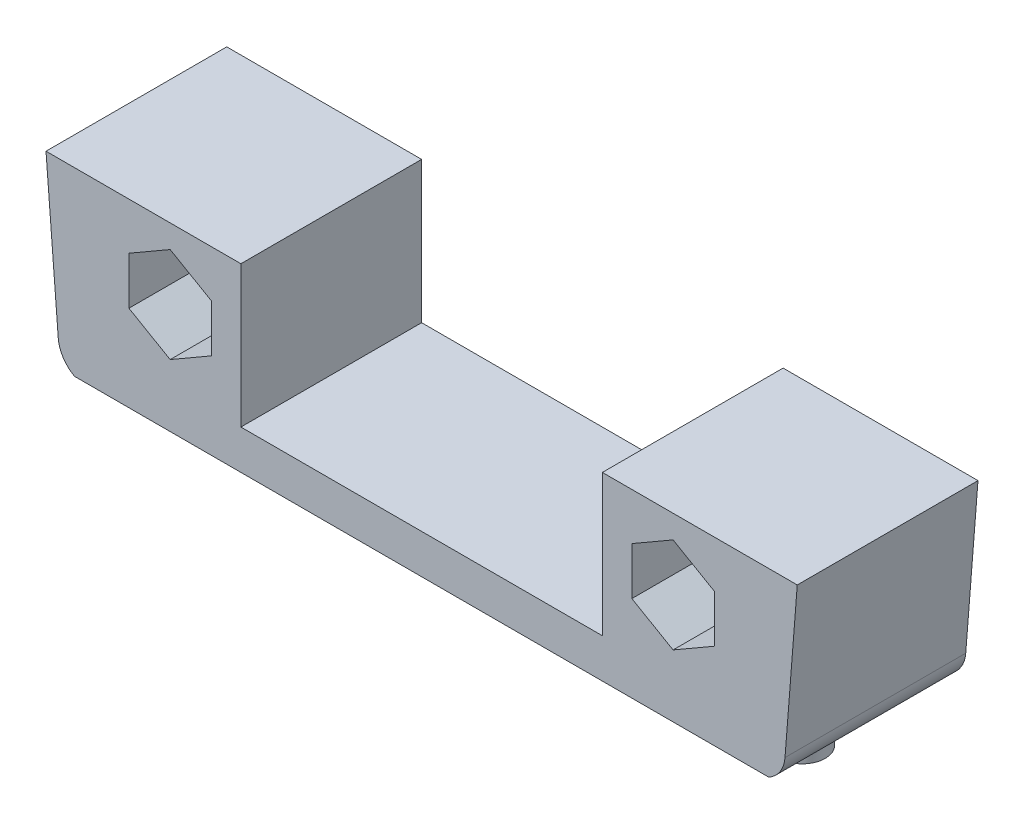
SolidWorks part; units mm, degrees
ref_plane "Front Plane" through (0, 0, 0) normal (0, 0, 1) x (1, 0, 0)
ref_plane "Top Plane" through (0, 0, 0) normal (0, 1, 0) x (1, 0, 0)
ref_plane "Right Plane" through (0, 0, 0) normal (1, 0, 0) x (0, 0, -1)
sketch "Sketch1" plane through (0, 0, 0) normal (0, 0, 1) x (1, 0, 0)
  line L0 (-23.9007, -76.5) -> (23.9007, -76.5)
  line L1 (-16, -84.0311) -> (-13.375, -82.5155)
  line L2 (-13.375, -82.5155) -> (-13.375, -79.4845)
  line L3 (-13.375, -79.4845) -> (-16, -77.9689)
  line L4 (-16, -77.9689) -> (-18.625, -79.4845)
  line L5 (-18.625, -79.4845) -> (-18.625, -82.5155)
  line L6 (-18.625, -82.5155) -> (-16, -84.0311)
  line L7 (16, -84.0311) -> (18.625, -82.5155)
  line L8 (18.625, -82.5155) -> (18.625, -79.4845)
  line L9 (18.625, -79.4845) -> (16, -77.9689)
  line L10 (16, -77.9689) -> (13.375, -79.4845)
  line L11 (13.375, -79.4845) -> (13.375, -82.5155)
  line L12 (13.375, -82.5155) -> (16, -84.0311)
  line L13 (-20.5, -85.5) -> (-11.5, -85.5)
  line L14 (-20.5, -85.5) -> (-20.5, -76.5)
  line L15 (-20.5, -76.5) -> (-11.5, -76.5)
  line L16 (-11.5, -85.5) -> (-11.5, -76.5)
  line L17 (-20.5, -85.5) -> (-11.5, -76.5) construction
  line L18 (-24.5714, 68.9048) -> (-33.6515, 43.9576)
  line L19 (-33.4302, 42.1552) -> (-25.3419, 30.1639)
  line L20 (-25, 29.0455) -> (-25, -29.0455)
  line L21 (-25.3419, -30.1639) -> (-33.4302, -42.1552)
  line L22 (-33.6515, -43.9576) -> (-24.5714, -68.9048)
  line L23 (-24.457, -69.4319) -> (-23.1215, -86.4007)
  line L24 (-21.475, -88.2134) -> (0, -92)
  line L25 (0, -92) -> (21.475, -88.2134)
  line L26 (23.1215, -86.4007) -> (24.457, -69.4319)
  line L27 (24.5714, -68.9048) -> (33.6515, -43.9576)
  line L28 (33.4302, -42.1552) -> (25.3419, -30.1639)
  line L29 (25, -29.0455) -> (25, 29.0455)
  line L30 (25.3419, 30.1639) -> (33.4302, 42.1552)
  line L31 (33.6515, 43.9576) -> (24.5714, 68.9048)
  line L32 (24.457, 69.4319) -> (23.1215, 86.4007)
  line L33 (21.475, 88.2134) -> (0, 92)
  line L34 (0, 92) -> (-21.475, 88.2134)
  line L35 (-23.1215, 86.4007) -> (-24.457, 69.4319)
  line L36 (-24.5714, 68.9048) -> (-33.6515, 43.9576)
  line L37 (-33.4302, 42.1552) -> (-25.3419, 30.1639)
  line L38 (-25, 29.0455) -> (-25, -29.0455)
  line L39 (-25.3419, -30.1639) -> (-33.4302, -42.1552)
  line L40 (-33.6515, -43.9576) -> (-24.5714, -68.9048)
  line L41 (-24.457, -69.4319) -> (-23.1215, -86.4007)
  line L42 (-21.475, -88.2134) -> (0, -92)
  line L43 (0, -92) -> (21.475, -88.2134)
  line L44 (23.1215, -86.4007) -> (24.457, -69.4319)
  line L45 (24.5714, -68.9048) -> (33.6515, -43.9576)
  line L46 (33.4302, -42.1552) -> (25.3419, -30.1639)
  line L47 (25, -29.0455) -> (25, 29.0455)
  line L48 (25.3419, 30.1639) -> (33.4302, 42.1552)
  line L49 (33.6515, 43.9576) -> (24.5714, 68.9048)
  line L50 (24.457, 69.4319) -> (23.1215, 86.4007)
  line L51 (21.475, 88.2134) -> (0, 92)
  line L52 (0, 92) -> (-21.475, 88.2134)
  line L53 (-23.1215, 86.4007) -> (-24.457, 69.4319)
  line L54 (-20.5, -76.5) -> (-11.5, -85.5) construction
  line L55 (20.5, -76.5) -> (11.5, -76.5)
  line L56 (20.5, -76.5) -> (20.5, -85.5)
  line L57 (20.5, -85.5) -> (11.5, -85.5)
  line L58 (11.5, -76.5) -> (11.5, -85.5)
  line L59 (20.5, -76.5) -> (11.5, -85.5) construction
  line L60 (20.5, -85.5) -> (11.5, -76.5) construction
  line L61 (0, -92) -> (0, -76.5) construction
  line L66 (-11.5, -85.5) -> (11.5, -85.5)
  circle A0 centre (-16, -81) radius 1.5 construction
  circle A1 centre (-16, -81) radius 1.5
  circle A2 centre (16, -81) radius 1.5 construction
  circle A3 centre (16, -81) radius 1.5
  circle A4 centre (-16, -81) radius 2.625 construction
  circle A5 centre (16, -81) radius 2.625 construction
  arc A16 (-24.5714, 68.9048) -> (-24.457, 69.4319) centre (-26.4508, 69.5889) ccw
  arc A17 (-33.6515, 43.9576) -> (-33.4302, 42.1552) centre (-31.7721, 43.2736) ccw
  arc A18 (-25, 29.0455) -> (-25.3419, 30.1639) centre (-27, 29.0455) ccw
  arc A19 (-25.3419, -30.1639) -> (-25, -29.0455) centre (-27, -29.0455) ccw
  arc A20 (-33.4302, -42.1552) -> (-33.6515, -43.9576) centre (-31.7721, -43.2736) ccw
  arc A21 (-24.457, -69.4319) -> (-24.5714, -68.9048) centre (-26.4508, -69.5889) ccw
  arc A22 (-23.1215, -86.4007) -> (-21.475, -88.2134) centre (-21.1277, -86.2438) ccw
  arc A23 (21.475, -88.2134) -> (23.1215, -86.4007) centre (21.1277, -86.2438) ccw
  arc A24 (24.5714, -68.9048) -> (24.457, -69.4319) centre (26.4508, -69.5889) ccw
  arc A25 (33.6515, -43.9576) -> (33.4302, -42.1552) centre (31.7721, -43.2736) ccw
  arc A26 (25, -29.0455) -> (25.3419, -30.1639) centre (27, -29.0455) ccw
  arc A27 (25.3419, 30.1639) -> (25, 29.0455) centre (27, 29.0455) ccw
  arc A28 (33.4302, 42.1552) -> (33.6515, 43.9576) centre (31.7721, 43.2736) ccw
  arc A29 (24.457, 69.4319) -> (24.5714, 68.9048) centre (26.4508, 69.5889) ccw
  arc A30 (23.1215, 86.4007) -> (21.475, 88.2134) centre (21.1277, 86.2438) ccw
  arc A31 (-21.475, 88.2134) -> (-23.1215, 86.4007) centre (-21.1277, 86.2438) ccw
  arc A32 (-24.5714, 68.9048) -> (-24.457, 69.4319) centre (-26.4508, 69.5889) ccw
  arc A33 (-33.6515, 43.9576) -> (-33.4302, 42.1552) centre (-31.7721, 43.2736) ccw
  arc A34 (-25, 29.0455) -> (-25.3419, 30.1639) centre (-27, 29.0455) ccw
  arc A35 (-25.3419, -30.1639) -> (-25, -29.0455) centre (-27, -29.0455) ccw
  arc A36 (-33.4302, -42.1552) -> (-33.6515, -43.9576) centre (-31.7721, -43.2736) ccw
  arc A37 (-24.457, -69.4319) -> (-24.5714, -68.9048) centre (-26.4508, -69.5889) ccw
  arc A38 (-23.1215, -86.4007) -> (-21.475, -88.2134) centre (-21.1277, -86.2438) ccw
  arc A39 (21.475, -88.2134) -> (23.1215, -86.4007) centre (21.1277, -86.2438) ccw
  arc A40 (24.5714, -68.9048) -> (24.457, -69.4319) centre (26.4508, -69.5889) ccw
  arc A41 (33.6515, -43.9576) -> (33.4302, -42.1552) centre (31.7721, -43.2736) ccw
  arc A42 (25, -29.0455) -> (25.3419, -30.1639) centre (27, -29.0455) ccw
  arc A43 (25.3419, 30.1639) -> (25, 29.0455) centre (27, 29.0455) ccw
  arc A44 (33.4302, 42.1552) -> (33.6515, 43.9576) centre (31.7721, 43.2736) ccw
  arc A45 (24.457, 69.4319) -> (24.5714, 68.9048) centre (26.4508, 69.5889) ccw
  arc A46 (23.1215, 86.4007) -> (21.475, 88.2134) centre (21.1277, 86.2438) ccw
  arc A47 (-21.475, 88.2134) -> (-23.1215, 86.4007) centre (-21.1277, 86.2438) ccw
  dimension "D2" = 5.25
  dimension "D3" = 15.5
  dimension "D1" = 0
extrude "Boss-Extrude1" add sketch "Sketch1" along normal blind 11.5
ref_plane "Plane1" through (0, -92, 0) normal (0, 1, 0) x (1, 0, 0)
sketch "Sketch2" plane through (0, -92, 0) normal (0, 1, 0) x (1, 0, 0)
  line L0 (-23.9007, -5.75) -> (23.9007, -5.75) construction
  line L1 (-23.9007, -11.5) -> (-23.9007, 0) construction
  line L2 (23.9007, -11.5) -> (23.9007, 0) construction
  line L3 (0, -11.5) -> (0, 0) construction
  line L4 (-22.75, -11.5) -> (22.75, -11.5)
  line L5 (-22.75, -11.5) -> (-22.75, -2.25)
  line L6 (-22.75, -2.25) -> (22.75, -2.25)
  line L7 (22.75, -11.5) -> (22.75, -2.25)
  line L8 (-22.75, -11.5) -> (22.75, -2.25) construction
  line L9 (-22.75, -2.25) -> (22.75, -11.5) construction
  line L10 (-21.475, -11.5) -> (0, -11.5) construction
  point P6 (0, -6.875)
  dimension "D1" = 45.5
  dimension "D2" = 9.25
extrude "Cut-Extrude1" cut sketch "Sketch2" along normal blind 4
sketch "Sketch3" plane through (0, -88, 0) normal (0, -1, 0) x (1, 0, 0)
  line L0 (-22.0846, 6.875) -> (22.0846, 6.875) construction
  line L1 (-22.0846, 11.5) -> (-22.0846, 2.25) construction
  line L2 (22.0846, 2.25) -> (22.0846, 11.5) construction
  line L3 (0, 11.5) -> (0, 2.25) construction
  line L4 (-22.0846, 11.5) -> (22.0846, 11.5) construction
  line L5 (22.0846, 2.25) -> (-22.0846, 2.25) construction
  circle A0 centre (-19.6, 6.875) radius 1.45
  circle A1 centre (19.6, 6.875) radius 1.45
  dimension "D1" = 2.9
  dimension "D2" = 39.2
extrude "Boss-Extrude2" add sketch "Sketch3" along normal blind 1.8
ref_plane "Plane2" through (0, -90.5, 0) normal (0, -1, 0) x (-1, 0, 0)
sketch "Sketch4" plane through (0, -92, 0) normal (0, 1, 0) x (1, 0, 0)
  line L0 (0, -2.25) -> (21.475, -2.25) construction
  line L1 (7.2846, -2.25) -> (4.2846, -2.25)
  line L2 (7.2846, -2.25) -> (7.2846, 0)
  line L3 (7.2846, 0) -> (4.2846, 0)
  line L4 (4.2846, -2.25) -> (4.2846, 0)
  line L5 (0, 0) -> (21.475, 0) construction
  line L6 (5.7846, -2.25) -> (5.7846, 0) construction
  line L7 (22.0846, -2.25) -> (22.0846, -11.5) construction
  dimension "D1" = 16.3
  dimension "D2" = 3
extrude "Cut-Extrude2" cut sketch "Sketch4" along normal up to next
